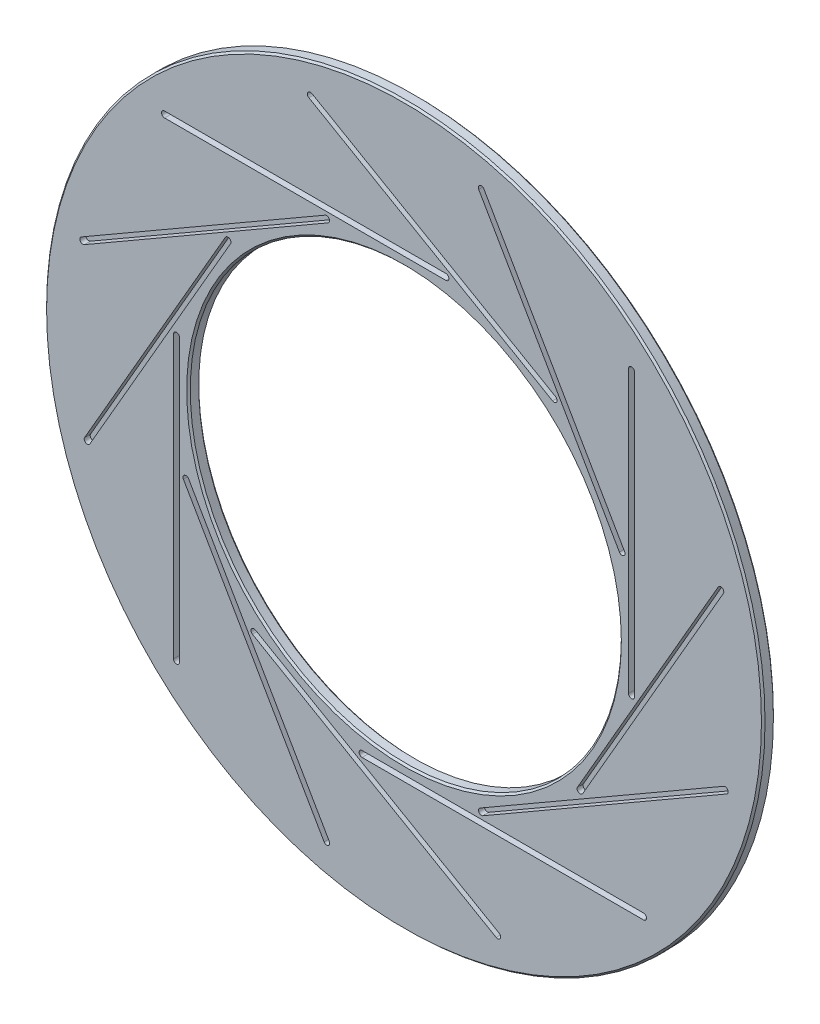
SolidWorks part; units mm, degrees
ref_plane "Front Plane" through (0, 0, 0) normal (0, 0, 1) x (1, 0, 0)
ref_plane "Top Plane" through (0, 0, 0) normal (0, 1, 0) x (1, 0, 0)
ref_plane "Right Plane" through (0, 0, 0) normal (1, 0, 0) x (0, 0, -1)
sketch "Sketch1" plane through (0, 0, 0) normal (0, 0, 1) x (1, 0, 0)
  circle A0 centre (0, 0) radius 36
  circle A1 centre (0, 0) radius 60
  dimension "D1" = 72
  dimension "D2" = 120
extrude "Boss-Extrude1" add sketch "Sketch1" along normal blind 2
sketch "Sketch2" plane through (0, 0, 2) normal (0, 0, 1) x (1, 0, 0)
  line L0 (0, 0) -> (0, 38) construction
  line L1 (-40, 38) -> (7, 38) construction
  line L2 (-40, 38.5) -> (7, 38.5)
  line L3 (-40, 37.5) -> (7, 37.5)
  circle A0 centre (0, 0) radius 38 construction
  arc A1 (-40, 38.5) -> (-40, 37.5) centre (-40, 38) ccw
  arc A2 (7, 37.5) -> (7, 38.5) centre (7, 38) ccw
  point P6 (-16.5, 38)
  dimension "D1" = 76
  dimension "D2" = 0.5
  dimension "D3" = 7
  dimension "D4" = 47
extrude "Cut-Extrude1" cut sketch "Sketch2" against normal blind 1
pattern_circular "CirPattern1" count 12 over 360 about axis through (0, 0, 0) along (0, 0, 1) of "Cut-Extrude1"
chamfer "Chamfer1" distance 0.3 angle 45 4 edges at (60, 0, 0) (60, 0, 2) (36, 0, 0) (36, 0, 2)
